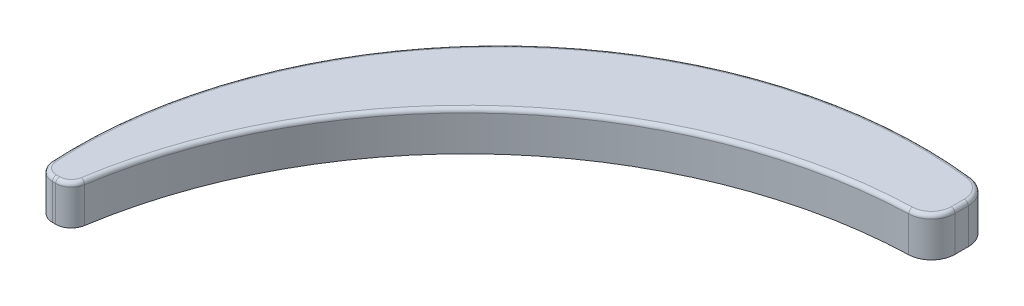
SolidWorks part; units mm, degrees
ref_plane "Спереди" through (0, 0, 0) normal (0, 0, 1) x (1, 0, 0)
ref_plane "Сверху" through (0, 0, 0) normal (0, 1, 0) x (1, 0, 0)
ref_plane "Справа" through (0, 0, 0) normal (1, 0, 0) x (0, 0, -1)
sketch "Эскиз1" plane through (0, 0, 0) normal (0, 1, 0) x (1, 0, 0)
  line L0 (-25.4341, 5.9442) -> (-25.8399, 5.9442)
  line L1 (35.0869, 61.5225) -> (35.0869, 59.8439)
  arc A0 (32.1849, 56.8455) -> (-23.4581, 7.635) centre (34.0869, -1.3685) ccw
  arc A1 (32.4398, 64.5017) -> (-27.8368, 7.8317) centre (26.0869, 10.8675) ccw
  arc A2 (-25.4341, 5.9442) -> (-23.4581, 7.635) centre (-25.4341, 7.9442) ccw
  arc A3 (-27.8368, 7.8317) -> (-25.8399, 5.9442) centre (-25.8399, 7.9442) ccw
  arc A4 (35.0869, 61.5225) -> (32.4398, 64.5017) centre (32.0869, 61.5225) ccw
  arc A5 (32.1849, 56.8455) -> (35.0869, 59.8439) centre (32.0869, 59.8439) ccw
extrude "Бобышка-Вытянуть1" add sketch "Эскиз1" along normal blind 5
fillet "Скругление1" radius 0.5 8 edges at (-4.4994, 5, -42.2616) (-24.1337, 5, -6.4246) (-25.637, 5, -5.9442) (-27.2138, 5, -6.4908) (-10.9079, 5, -50.2168) (34.3295, 5, -63.5151) (35.0869, 5, -60.6832) (34.2426, 5, -57.7575)
